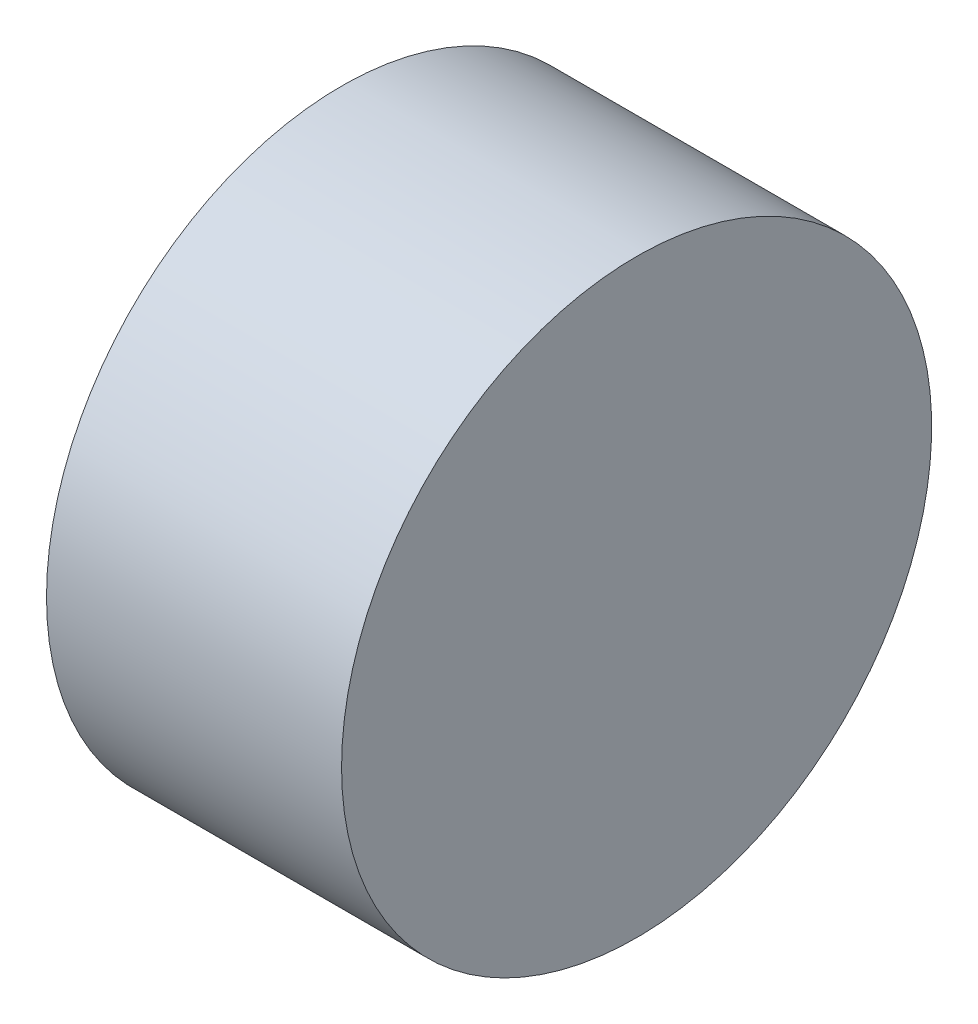
SolidWorks part; units mm, degrees
ref_plane "Front Plane" through (0, 0, 0) normal (0, 0, 1) x (1, 0, 0)
ref_plane "Top Plane" through (0, 0, 0) normal (0, 1, 0) x (1, 0, 0)
ref_plane "Right Plane" through (0, 0, 0) normal (1, 0, 0) x (0, 0, -1)
sketch "Axial profile (mm)" plane through (0, 0, 0) normal (0, 0, 1) x (1, 0, 0)
  line L0 (-110, 0) -> (75, 0) construction
  line L1 (143.7, 0) -> (148.7, 0)
  line L2 (148.7, 0) -> (148.7, 5)
  line L3 (148.7, 5) -> (143.7, 5)
  line L4 (143.7, 5) -> (143.7, 0)
revolve "Full revolution" add sketch "Axial profile (mm)" angle 360 about L0
